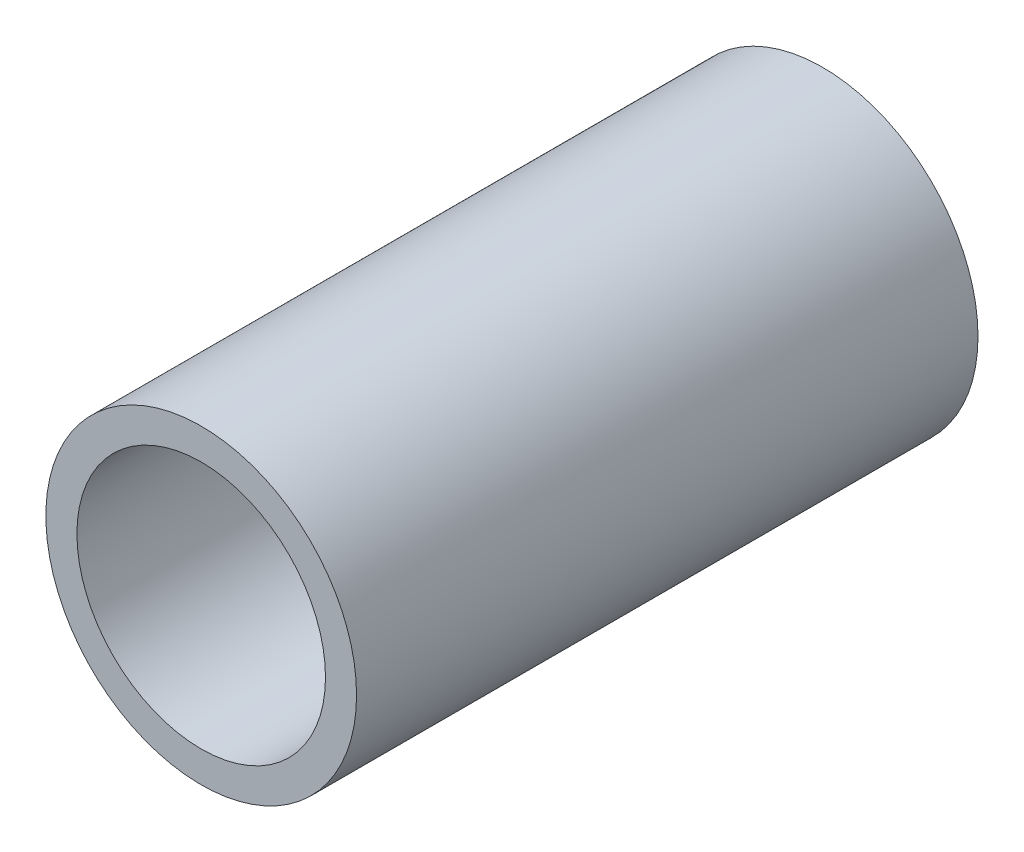
SolidWorks part; units mm, degrees
material "Brass"
ref_plane "Front Plane" through (0, 0, 0) normal (0, 0, 1) x (1, 0, 0)
ref_plane "Top Plane" through (0, 0, 0) normal (0, 1, 0) x (1, 0, 0)
ref_plane "Right Plane" through (0, 0, 0) normal (1, 0, 0) x (0, 0, -1)
sketch "Sketch1" plane through (0, 0, 0) normal (0, 0, 1) x (1, 0, 0)
  circle A0 centre (0, 0) radius 6.35
  circle A1 centre (0, 0) radius 7.9375
  dimension "D1" = 12.7
  dimension "D2" = 15.875
extrude "Boss-Extrude1" add sketch "Sketch1" along normal blind 31.75
